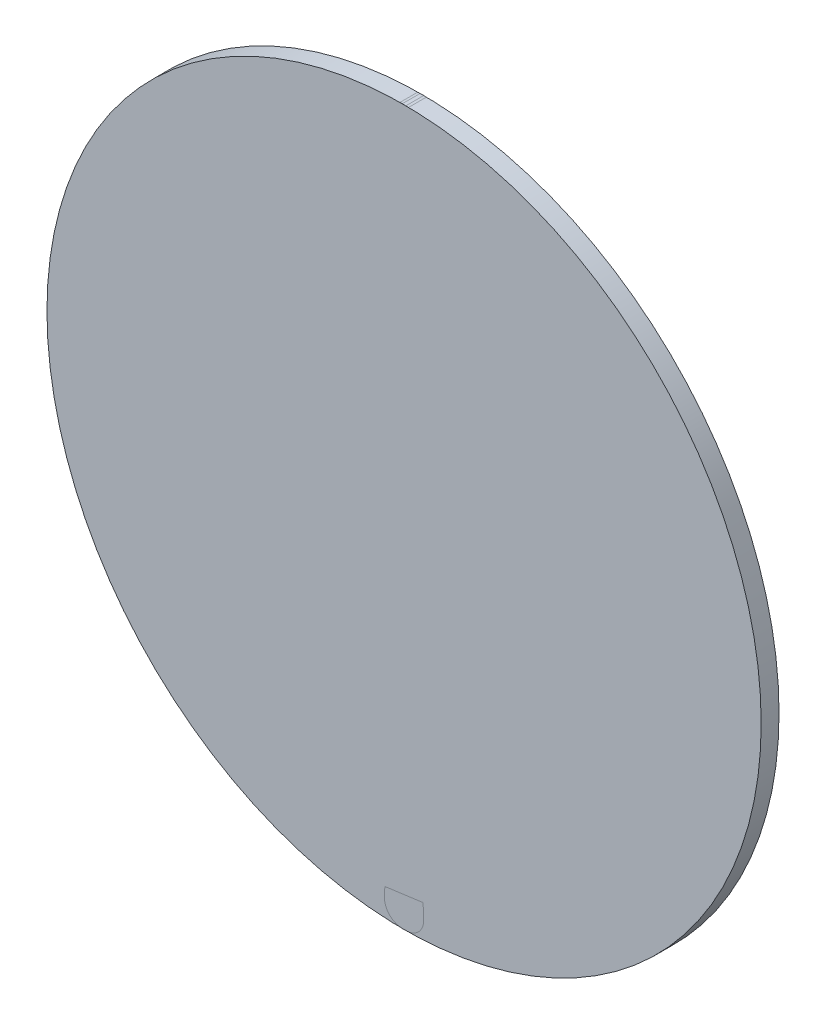
SolidWorks part; units mm, degrees
ref_plane "Front Plane" through (0, 0, 0) normal (1, 0, 0) x (0, 1, 0)
ref_plane "Top Plane" through (0, 0, 0) normal (0, 0, 1) x (0, 1, 0)
ref_plane "Right Plane" through (0, 0, 0) normal (0, 1, 0) x (-1, 0, 0)
sketch "Sketch1" plane through (0, 0, 0) normal (0, 0, 1) x (0, 1, 0)
  line L0 (0, 0) -> (-9.525, 0) construction
  line L1 (0, 9.525) -> (0, 0) construction
  line L2 (-9.2827, 2.1347) -> (-120.373, 6.985)
  line L3 (-127, 0.641) -> (-127, -0.641)
  line L4 (-9.2827, -2.1347) -> (-120.373, -6.985)
  line L5 (9.2827, -2.1347) -> (120.373, -6.985)
  line L6 (9.2827, 2.1347) -> (120.373, 6.985)
  line L7 (127, 0.641) -> (127, -0.641)
  arc A0 (-9.2827, -2.1347) -> (9.2827, -2.1347) centre (0, 0) ccw
  circle A1 centre (0, 0) radius 2.54
  arc A2 (-120.373, -6.985) -> (-127, -0.641) centre (-120.65, -0.641) cw
  arc A3 (-120.373, 6.985) -> (-127, 0.641) centre (-120.65, 0.641) ccw
  arc A4 (120.373, 6.985) -> (127, 0.641) centre (120.65, 0.641) cw
  arc A5 (120.373, -6.985) -> (127, -0.641) centre (120.65, -0.641) ccw
  arc A6 (9.2827, 2.1347) -> (-9.2827, 2.1347) centre (0, 0) ccw
  point P11 (-127, 0)
  point P12 (-127, -7.2743)
  point P15 (-127, 7.2743)
  point P16 (-187.2521, 14.1536)
  point P25 (127, 7.2743)
  point P26 (127, -7.2743)
  point P27 (127, 0)
  point P28 (14.7279, -4.9211)
  point P29 (-9.2608, 2.2277)
  point P30 (-9.2827, 0)
  point P31 (0, 0)
  dimension "D1" = 6.35
  dimension "D3" = 5.08
  dimension "D4" = 9.525
  dimension "D2" = 254
  dimension "D5" = 5
  dimension "D6" = 13.97
extrude "Boss-Extrude1" add sketch "Sketch1" along normal mid plane 6.35
sketch "Sketch2" plane through (0, 0, 3.175) normal (0, 0, 1) x (1, 0, 0)
  circle A0 centre (0, 0) radius 127.0016
extrude "Boss-Extrude2" add sketch "Sketch2" against normal up to surface (6.35 mm away) separate body up to face at (0, 0, -3.175)
